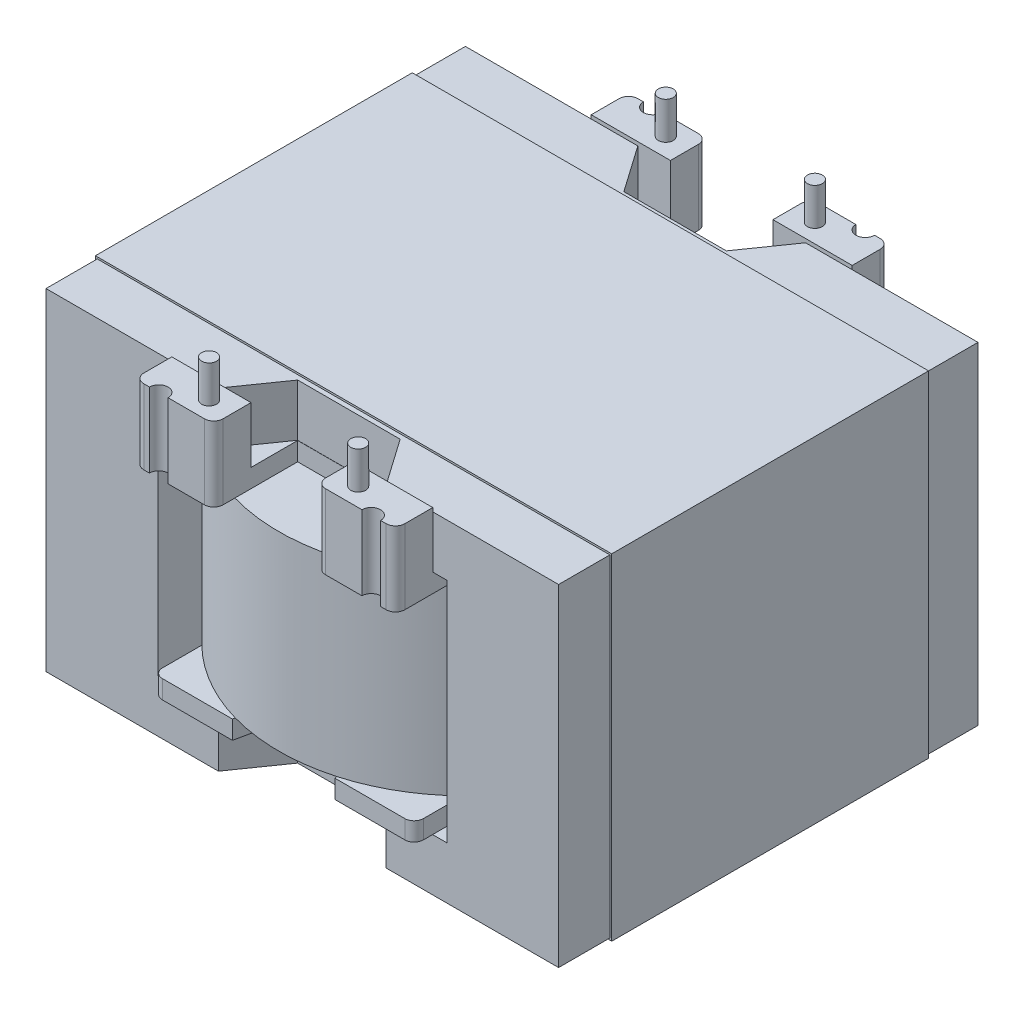
SolidWorks part; units mm, degrees
ref_plane "Спереди" through (0, 0, 0) normal (0, 0, 1) x (1, 0, 0)
ref_plane "Сверху" through (0, 0, 0) normal (0, 1, 0) x (1, 0, 0)
ref_plane "Справа" through (0, 0, 0) normal (1, 0, 0) x (0, 0, -1)
sketch "Эскиз1" plane through (0, 0, 0) normal (0, 1, 0) x (1, 0, 0)
  line L1 (-13.75, -11.25) -> (13.75, -11.25)
  line L2 (-13.75, -11.25) -> (-13.75, 11.25)
  line L3 (-13.75, 11.25) -> (13.75, 11.25)
  line L4 (13.75, -11.25) -> (13.75, 11.25)
  line L5 (-13.75, -11.25) -> (13.75, 11.25) construction
  line L6 (-13.75, 11.25) -> (13.75, -11.25) construction
  point P0 (0, 0)
  dimension "D1" = 27.5
  dimension "D2" = 22.5
extrude "Бобышка-Вытянуть1" add sketch "Эскиз1" along normal blind 17.8
sketch "Эскиз3" plane through (0, 0, 0) normal (0, 0, 1) x (1, 0, 0)
  line L0 (13.75, 17.8) -> (13.75, 0) construction
  line L1 (-7.75, 15) -> (7.75, 15)
  line L2 (-7.75, 15) -> (-7.75, 2.8)
  line L3 (-7.75, 2.8) -> (7.75, 2.8)
  line L4 (7.75, 15) -> (7.75, 2.8)
  line L5 (-7.75, 15) -> (7.75, 2.8) construction
  line L6 (-7.75, 2.8) -> (7.75, 15) construction
  line L7 (13.75, 0) -> (-13.75, 0) construction
  point P0 (0, 8.9)
  point P11 (13.75, 8.9)
  dimension "D1" = 2.8
  dimension "D2" = 15.5
extrude "Вырез-Вытянуть1" cut sketch "Эскиз3" against normal through all both and the other way through all
sketch "Эскиз4" plane through (0, 0, 0) normal (0, 1, 0) x (1, 0, 0)
  line L0 (-4.5, 11.25) -> (-2.75, 8.75)
  line L1 (13.75, 11.25) -> (-13.75, 11.25) construction
  line L2 (-2.75, 8.75) -> (2.75, 8.75)
  line L3 (2.75, 8.75) -> (4.5, 11.25)
  line L4 (4.5, 11.25) -> (-4.5, 11.25)
  line L5 (-18.0038, 0) -> (17.3641, 0) construction
  line L6 (4.5, -11.25) -> (-4.5, -11.25)
  line L7 (2.75, -8.75) -> (4.5, -11.25)
  line L8 (-2.75, -8.75) -> (2.75, -8.75)
  line L9 (-4.5, -11.25) -> (-2.75, -8.75)
  point P4 (0, 8.75)
  point P7 (0, 11.25)
  dimension "D1" = 9
  dimension "D2" = 2.5
  dimension "D3" = 5.5
extrude "Вырез-Вытянуть2" cut sketch "Эскиз4" along normal through all
ref_plane "Плоскость1" through (0, 8.9, 0) normal (0, 1, 0) x (1, 0, 0)
sketch "Эскиз2" plane through (0, 8.9, 0) normal (0, 1, 0) x (1, 0, 0)
  line L0 (0, -2.5) -> (0, 2.5) construction
  line L1 (-10, -2.5) -> (-10, 2.5)
  line L2 (10, -2.5) -> (10, 2.5)
  arc A0 (-10, -2.5) -> (10, -2.5) centre (0, -2.5) ccw
  arc A1 (10, 2.5) -> (-10, 2.5) centre (0, 2.5) ccw
  point P3 (0, 0)
  dimension "D2" = 25
  dimension "D1" = 20
extrude "Бобышка-Вытянуть2" add sketch "Эскиз2" against normal offset from surface 1 and the other way offset from surface (5.1 mm away) 1 up to face at (0, 2.8, 0) other way up to face at (0, 15, 0)
sketch "Эскиз5" plane through (0, 3.8, 0) normal (0, -1, 0) x (1, 0, 0)
  line L0 (7, 11.75) -> (7, -11.75)
  line L1 (6.5, -12.25) -> (2.75, -12.25)
  line L2 (2.75, -12.25) -> (2.0847, -9.1452)
  line L3 (1.5958, -8.75) -> (-1.5958, -8.75)
  line L4 (-2.0847, -9.1452) -> (-2.75, -12.25)
  line L5 (-2.75, -12.25) -> (-6.5, -12.25)
  line L6 (-7, -11.75) -> (-7, 11.75)
  line L10 (7, 0) -> (-7, 0) construction
  line L12 (-2.75, -8.75) -> (2.75, -8.75) construction
  line L13 (-4.5, -11.25) -> (-13.75, -11.25) construction
  line L14 (-2.75, 12.25) -> (-6.5, 12.25)
  line L15 (-2.0847, 9.1452) -> (-2.75, 12.25)
  line L16 (1.5958, 8.75) -> (-1.5958, 8.75)
  line L17 (2.75, 12.25) -> (2.0847, 9.1452)
  line L18 (6.5, 12.25) -> (2.75, 12.25)
  arc A0 (2.0847, -9.1452) -> (1.5958, -8.75) centre (1.5958, -9.25) ccw
  arc A1 (-1.5958, -8.75) -> (-2.0847, -9.1452) centre (-1.5958, -9.25) ccw
  arc A2 (7, -11.75) -> (6.5, -12.25) centre (6.5, -11.75) cw
  arc A3 (-6.5, -12.25) -> (-7, -11.75) centre (-6.5, -11.75) cw
  arc A4 (-6.5, 12.25) -> (-7, 11.75) centre (-6.5, 11.75) ccw
  arc A5 (7, 11.75) -> (6.5, 12.25) centre (6.5, 11.75) ccw
  arc A6 (-1.5958, 8.75) -> (-2.0847, 9.1452) centre (-1.5958, 9.25) cw
  arc A7 (2.0847, 9.1452) -> (1.5958, 8.75) centre (1.5958, 9.25) cw
  point P0 (0, -8.75)
  point P18 (2, -8.75)
  point P21 (-2, -8.75)
  point P40 (-2, 8.75)
  point P41 (2, 8.75)
  dimension "D5" = 0.5
  dimension "D1" = 5.5
  dimension "D2" = 4
  dimension "D3" = 1
  dimension "D4" = 14
extrude "Бобышка-Вытянуть3" add sketch "Эскиз5" along normal offset from surface (0.99 mm away) 0.01 up to face at (0, 2.8, 0)
sketch "Эскиз6" plane through (0, 14, 0) normal (0, 1, 0) x (1, 0, 0)
  line L0 (-7, -12.75) -> (-7, 12.75)
  line L1 (-7, 9.6414) -> (-7, 11.75) construction
  line L2 (-6.5, 13.25) -> (-6.2, 13.25)
  line L3 (-2.75, 12.75) -> (-2.75, 8.75)
  line L4 (-2.75, 8.75) -> (2.75, 8.75)
  line L5 (2.75, 8.75) -> (2.75, 12.75)
  line L6 (3.25, 13.25) -> (5.2, 13.25)
  line L7 (7, 12.75) -> (7, -12.75)
  line L8 (7, 0) -> (-7, 0) construction
  line L9 (13.75, 11.25) -> (4.5, 11.25) construction
  line L10 (-1.5958, 8.75) -> (1.5958, 8.75) construction
  line L11 (0, 8.75) -> (0, -8.75) construction
  line L12 (-5.2, 13.25) -> (-3.25, 13.25)
  line L13 (6.2, 13.25) -> (6.5, 13.25)
  line L14 (6.2, -13.25) -> (6.5, -13.25)
  line L15 (-5.2, -13.25) -> (-3.25, -13.25)
  line L16 (3.25, -13.25) -> (5.2, -13.25)
  line L17 (2.75, -8.75) -> (2.75, -12.75)
  line L18 (-2.75, -8.75) -> (2.75, -8.75)
  line L19 (-2.75, -12.75) -> (-2.75, -8.75)
  line L20 (-6.5, -13.25) -> (-6.2, -13.25)
  arc A0 (-6.2, 13.25) -> (-5.2, 13.25) centre (-5.7, 13.25) ccw
  arc A1 (6.2, 13.25) -> (5.2, 13.25) centre (5.7, 13.25) cw
  arc A2 (-3.25, 13.25) -> (-2.75, 12.75) centre (-3.25, 12.75) cw
  arc A3 (-7, 12.75) -> (-6.5, 13.25) centre (-6.5, 12.75) cw
  arc A4 (6.5, 13.25) -> (7, 12.75) centre (6.5, 12.75) cw
  arc A5 (2.75, 12.75) -> (3.25, 13.25) centre (3.25, 12.75) cw
  arc A6 (2.75, -12.75) -> (3.25, -13.25) centre (3.25, -12.75) ccw
  arc A7 (6.5, -13.25) -> (7, -12.75) centre (6.5, -12.75) ccw
  arc A8 (-7, -12.75) -> (-6.5, -13.25) centre (-6.5, -12.75) ccw
  arc A9 (-3.25, -13.25) -> (-2.75, -12.75) centre (-3.25, -12.75) ccw
  arc A10 (6.2, -13.25) -> (5.2, -13.25) centre (5.7, -13.25) ccw
  arc A11 (-6.2, -13.25) -> (-5.2, -13.25) centre (-5.7, -13.25) cw
  point P0 (0, 8.75)
  point P34 (0, 0)
  dimension "D2" = 0.5
  dimension "D3" = 1.3
  dimension "D4" = 0.5
  dimension "D1" = 2
extrude "Бобышка-Вытянуть4" add sketch "Эскиз6" along normal offset from surface (0.99 mm away) 0.01 up to face at (0, 15, 0)
sketch "Эскиз7" plane through (0, 14.99, 0) normal (0, 1, 0) x (1, 0, 0)
  line L0 (-7, 11.25) -> (-2.75, 11.25)
  line L1 (-4.5, 11.25) -> (-13.75, 11.25) construction
  line L2 (7, 11.25) -> (2.75, 11.25)
  line L3 (13.75, 11.25) -> (4.5, 11.25) construction
  line L4 (7, -11.25) -> (2.75, -11.25)
  line L5 (4.5, -11.25) -> (13.75, -11.25) construction
  line L6 (-7, -11.25) -> (-2.75, -11.25)
  line L7 (-13.75, -11.25) -> (-4.5, -11.25) construction
  line L8 (-7, -11.25) -> (-7, -12.75)
  line L9 (7, 11.25) -> (7, 12.75)
  line L16 (2.75, 12.75) -> (2.75, 8.75)
  line L17 (2.75, 8.75) -> (-2.75, 8.75)
  line L18 (-2.75, 8.75) -> (-2.75, 12.75)
  line L19 (-3.25, 13.25) -> (-5.2, 13.25)
  line L20 (-6.2, 13.25) -> (-6.5, 13.25)
  line L21 (-7, 12.75) -> (-7, -12.75)
  line L22 (-6.5, -13.25) -> (-6.2, -13.25)
  line L23 (-5.2, -13.25) -> (-3.25, -13.25)
  line L24 (-2.75, -12.75) -> (-2.75, -8.75)
  line L25 (-2.75, -8.75) -> (2.75, -8.75)
  line L26 (2.75, -8.75) -> (2.75, -12.75)
  line L27 (3.25, -13.25) -> (5.2, -13.25)
  line L28 (6.2, -13.25) -> (6.5, -13.25)
  line L29 (7, -12.75) -> (7, 12.75)
  line L30 (6.5, 13.25) -> (6.2, 13.25)
  line L31 (5.2, 13.25) -> (3.25, 13.25)
  line L32 (2.75, 12.75) -> (2.75, 11.25)
  line L34 (-2.75, 11.25) -> (-2.75, 12.75)
  line L35 (-3.25, 13.25) -> (-5.2, 13.25)
  line L36 (-6.2, 13.25) -> (-6.5, 13.25)
  line L37 (-7, 12.75) -> (-7, 11.25)
  line L38 (-6.5, -13.25) -> (-6.2, -13.25)
  line L39 (-5.2, -13.25) -> (-3.25, -13.25)
  line L40 (-2.75, -12.75) -> (-2.75, -11.25)
  line L42 (2.75, -11.25) -> (2.75, -12.75)
  line L43 (3.25, -13.25) -> (5.2, -13.25)
  line L44 (6.2, -13.25) -> (6.5, -13.25)
  line L45 (7, -12.75) -> (7, -11.25)
  line L46 (6.5, 13.25) -> (6.2, 13.25)
  line L47 (5.2, 13.25) -> (3.25, 13.25)
  arc A12 (-2.75, 12.75) -> (-3.25, 13.25) centre (-3.25, 12.75) ccw
  arc A13 (-6.2, 13.25) -> (-5.2, 13.25) centre (-5.7, 13.25) ccw
  arc A14 (-6.5, 13.25) -> (-7, 12.75) centre (-6.5, 12.75) ccw
  arc A15 (-7, -12.75) -> (-6.5, -13.25) centre (-6.5, -12.75) ccw
  arc A16 (-5.2, -13.25) -> (-6.2, -13.25) centre (-5.7, -13.25) ccw
  arc A17 (-3.25, -13.25) -> (-2.75, -12.75) centre (-3.25, -12.75) ccw
  arc A18 (2.75, -12.75) -> (3.25, -13.25) centre (3.25, -12.75) ccw
  arc A19 (6.2, -13.25) -> (5.2, -13.25) centre (5.7, -13.25) ccw
  arc A20 (6.5, -13.25) -> (7, -12.75) centre (6.5, -12.75) ccw
  arc A21 (7, 12.75) -> (6.5, 13.25) centre (6.5, 12.75) ccw
  arc A22 (5.2, 13.25) -> (6.2, 13.25) centre (5.7, 13.25) ccw
  arc A23 (3.25, 13.25) -> (2.75, 12.75) centre (3.25, 12.75) ccw
  arc A24 (-2.75, 12.75) -> (-3.25, 13.25) centre (-3.25, 12.75) ccw
  arc A25 (-6.2, 13.25) -> (-5.2, 13.25) centre (-5.7, 13.25) ccw
  arc A26 (-6.5, 13.25) -> (-7, 12.75) centre (-6.5, 12.75) ccw
  arc A27 (-7, -12.75) -> (-6.5, -13.25) centre (-6.5, -12.75) ccw
  arc A28 (-5.2, -13.25) -> (-6.2, -13.25) centre (-5.7, -13.25) ccw
  arc A29 (-3.25, -13.25) -> (-2.75, -12.75) centre (-3.25, -12.75) ccw
  arc A30 (2.75, -12.75) -> (3.25, -13.25) centre (3.25, -12.75) ccw
  arc A31 (6.2, -13.25) -> (5.2, -13.25) centre (5.7, -13.25) ccw
  arc A32 (6.5, -13.25) -> (7, -12.75) centre (6.5, -12.75) ccw
  arc A33 (7, 12.75) -> (6.5, 13.25) centre (6.5, 12.75) ccw
  arc A34 (5.2, 13.25) -> (6.2, 13.25) centre (5.7, 13.25) ccw
  arc A35 (3.25, 13.25) -> (2.75, 12.75) centre (3.25, 12.75) ccw
  dimension "D1" = 0
extrude "Бобышка-Вытянуть5" add sketch "Эскиз7" along normal offset from surface (3.01 mm away) 0.2 up to face at (0, 17.8, 0) offset beyond the face yes
sketch "Эскиз8" plane through (0, 18, 0) normal (0, 1, 0) x (1, 0, 0)
  line L0 (4, -12.25) -> (-4, -12.25) construction
  line L1 (8.5905, 0) -> (-8.5905, 0) construction
  line L2 (-3.25, -13.25) -> (-5.2, -13.25) construction
  circle A0 centre (4, -12.25) radius 0.4
  circle A1 centre (-4, -12.25) radius 0.4
  circle A2 centre (-4, 12.25) radius 0.4
  circle A3 centre (4, 12.25) radius 0.4
  point P6 (0, -12.25)
  dimension "D3" = 0.8
  dimension "D1" = 8
  dimension "D2" = 1
extrude "Бобышка-Вытянуть6" add sketch "Эскиз8" along normal blind 2
sketch "Эскиз9" plane through (0, 0, 0) normal (0, 0, 1) x (1, 0, 0)
  line L0 (-13.75, 17.8) -> (-13.75, 0) construction
  line L1 (4.5, 0) -> (13.75, 0) construction
  line L2 (7, 17.8) -> (13.75, 17.8) construction
  line L3 (13.75, 17.8) -> (13.75, 0) construction
  line L4 (-13.75, 17.8) -> (-13.75, 0)
  line L5 (-13.75, 0) -> (13.75, 0)
  line L6 (-13.75, 17.8) -> (13.75, 17.8)
  line L7 (13.75, 17.8) -> (13.75, 0)
  line L8 (-13.85, 17.9) -> (-13.85, -0.1)
  line L9 (-13.85, -0.1) -> (13.85, -0.1)
  line L10 (13.85, 17.9) -> (13.85, -0.1)
  line L11 (-13.85, 17.9) -> (13.85, 17.9)
  dimension "D1" = 0.1
extrude "Бобышка-Вытянуть7" add sketch "Эскиз9" along normal mid plane 17
